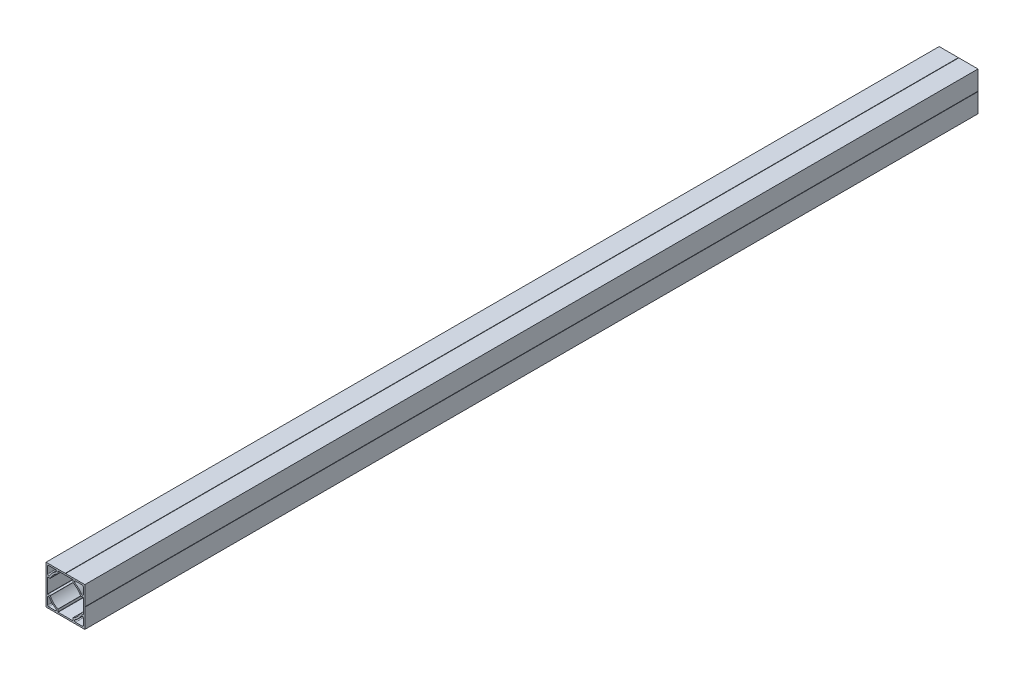
SolidWorks part; units mm, degrees
material "6061 Alloy"
ref_plane "Front Plane" through (0, 0, 0) normal (0, 0, 1) x (1, 0, 0)
ref_plane "Top Plane" through (0, 0, 0) normal (0, 1, 0) x (1, 0, 0)
ref_plane "Right Plane" through (0, 0, 0) normal (1, 0, 0) x (0, 0, -1)
other "Configuration Table"
sketch "Sketch1" plane through (0, 0, 0) normal (0, 0, 1) x (1, 0, 0)
  line L6 (1.7076, 1.016) -> (6.1029, 1.016)
  line L7 (1.016, 6.1029) -> (1.016, 1.7076)
  line L10 (25.4, 12.827) -> (25.4, 25.4)
  line L11 (25.4, 25.4) -> (12.827, 25.4)
  line L14 (12.573, 25.4) -> (0, 25.4)
  line L15 (0, 25.4) -> (0, 12.827)
  line L16 (0, 12.827) -> (0.127, 12.7)
  line L17 (0.127, 12.7) -> (0, 12.573)
  line L18 (0, 12.573) -> (0, 0)
  line L22 (12.827, 0) -> (25.4, 0)
  line L23 (25.4, 0) -> (25.4, 12.573)
  line L24 (1.143, 7.8105) -> (2.6421, 7.8105)
  line L25 (1.016, 17.4625) -> (1.016, 7.9375)
  line L26 (2.6421, 17.5895) -> (1.143, 17.5895)
  line L27 (1.016, 23.6924) -> (1.016, 19.2971)
  line L28 (6.1029, 24.384) -> (1.7076, 24.384)
  line L29 (17.5895, 22.7579) -> (17.5895, 24.257)
  line L30 (17.4625, 24.384) -> (7.9375, 24.384)
  line L31 (7.8105, 24.257) -> (7.8105, 22.7579)
  line L32 (23.6924, 24.384) -> (19.2971, 24.384)
  line L33 (24.384, 19.2971) -> (24.384, 23.6924)
  line L34 (22.7579, 7.8105) -> (24.257, 7.8105)
  line L35 (24.384, 7.9375) -> (24.384, 17.4625)
  line L36 (24.257, 17.5895) -> (22.7579, 17.5895)
  line L37 (24.384, 1.7076) -> (24.384, 6.1029)
  line L38 (19.2971, 1.016) -> (23.6924, 1.016)
  line L39 (7.8105, 2.6421) -> (7.8105, 1.143)
  line L40 (7.9375, 1.016) -> (17.4625, 1.016)
  line L41 (17.5895, 1.143) -> (17.5895, 2.6421)
  line L44 (12.827, 25.4) -> (12.7, 25.273)
  line L45 (12.7, 25.273) -> (12.573, 25.4)
  line L46 (25.4, 12.573) -> (25.273, 12.7)
  line L47 (25.273, 12.7) -> (25.4, 12.827)
  line L48 (12.573, 0) -> (12.7, 0.127)
  line L49 (12.7, 0.127) -> (12.827, 0)
  line L50 (12.573, 0) -> (0, 0)
  arc A14 (1.016, 1.7076) -> (1.7076, 1.016) centre (1.7076, 1.7076) ccw
  arc A15 (2.3006, 6.4588) -> (1.016, 6.1029) centre (1.7076, 6.1029) ccw
  arc A16 (2.3006, 6.4588) -> (6.4588, 2.3006) centre (12.7, 12.7) ccw
  arc A17 (6.1029, 1.016) -> (6.4588, 2.3006) centre (6.1029, 1.7076) ccw
  arc A18 (2.7558, 7.7402) -> (7.7402, 2.7558) centre (12.7, 12.7) ccw
  arc A19 (2.7558, 7.7402) -> (2.6421, 7.8105) centre (2.6421, 7.6835) ccw
  arc A20 (1.016, 7.9375) -> (1.143, 7.8105) centre (1.143, 7.9375) ccw
  arc A21 (1.143, 17.5895) -> (1.016, 17.4625) centre (1.143, 17.4625) ccw
  arc A22 (2.6421, 17.5895) -> (2.7558, 17.6598) centre (2.6421, 17.7165) ccw
  arc A23 (1.016, 19.2971) -> (2.3006, 18.9412) centre (1.7076, 19.2971) ccw
  arc A24 (6.4588, 23.0994) -> (2.3006, 18.9412) centre (12.7, 12.7) ccw
  arc A25 (6.4588, 23.0994) -> (6.1029, 24.384) centre (6.1029, 23.6924) ccw
  arc A26 (1.7076, 24.384) -> (1.016, 23.6924) centre (1.7076, 23.6924) ccw
  arc A27 (17.5895, 24.257) -> (17.4625, 24.384) centre (17.4625, 24.257) ccw
  arc A28 (17.5895, 22.7579) -> (17.6598, 22.6442) centre (17.7165, 22.7579) ccw
  arc A29 (7.9375, 24.384) -> (7.8105, 24.257) centre (7.9375, 24.257) ccw
  arc A30 (7.7402, 22.6442) -> (7.8105, 22.7579) centre (7.6835, 22.7579) ccw
  arc A31 (7.7402, 22.6442) -> (2.7558, 17.6598) centre (12.7, 12.7) ccw
  arc A32 (19.2971, 24.384) -> (18.9412, 23.0994) centre (19.2971, 23.6924) ccw
  arc A33 (23.0994, 18.9412) -> (18.9412, 23.0994) centre (12.7, 12.7) ccw
  arc A34 (23.0994, 18.9412) -> (24.384, 19.2971) centre (23.6924, 19.2971) ccw
  arc A35 (24.384, 23.6924) -> (23.6924, 24.384) centre (23.6924, 23.6924) ccw
  arc A36 (24.257, 7.8105) -> (24.384, 7.9375) centre (24.257, 7.9375) ccw
  arc A37 (22.7579, 7.8105) -> (22.6442, 7.7402) centre (22.7579, 7.6835) ccw
  arc A38 (24.384, 17.4625) -> (24.257, 17.5895) centre (24.257, 17.4625) ccw
  arc A39 (22.6442, 17.6598) -> (22.7579, 17.5895) centre (22.7579, 17.7165) ccw
  arc A40 (22.6442, 17.6598) -> (17.6598, 22.6442) centre (12.7, 12.7) ccw
  arc A41 (24.384, 6.1029) -> (23.0994, 6.4588) centre (23.6924, 6.1029) ccw
  arc A42 (18.9412, 2.3006) -> (23.0994, 6.4588) centre (12.7, 12.7) ccw
  arc A43 (18.9412, 2.3006) -> (19.2971, 1.016) centre (19.2971, 1.7076) ccw
  arc A44 (23.6924, 1.016) -> (24.384, 1.7076) centre (23.6924, 1.7076) ccw
  arc A45 (7.8105, 1.143) -> (7.9375, 1.016) centre (7.9375, 1.143) ccw
  arc A46 (7.8105, 2.6421) -> (7.7402, 2.7558) centre (7.6835, 2.6421) ccw
  arc A47 (17.4625, 1.016) -> (17.5895, 1.143) centre (17.4625, 1.143) ccw
  arc A48 (17.6598, 2.7558) -> (17.5895, 2.6421) centre (17.7165, 2.6421) ccw
  arc A49 (17.6598, 2.7558) -> (22.6442, 7.7402) centre (12.7, 12.7) ccw
  point P41 (12.7, 24.384)
  point P109 (12.7, 12.7)
  point P116 (12.7, 12.7)
  dimension "D1" = 25.4
  dimension "D2" = 1.016
  dimension "D3" = 4
  dimension "D4" = 1.016
  dimension "D7" = 0.127
  dimension "D12" = 11.1125
  dimension "D5" = 0.127
  dimension "D13" = 12.1285
  dimension "D6" = 9.525
  dimension "D8" = 135
  dimension "D9" = 5.7785
  dimension "D10" = 0.127
  dimension "D11" = 4
extrude "Boss-Extrude1" add sketch "Sketch1" along normal blind 584.2
sketch "Sketch2" [suppressed] plane through (0, 0, 0) normal (-1, 0, 0) x (0, 0, 1)
  line L0 (1193.8, 12.7) -> (0, 12.7) construction
  line L1 (0, 12.573) -> (0, 0) construction
  circle A0 centre (12.7, 12.7) radius 2.54
  dimension "D1" = 5.08
  dimension "D2" = 12.7
extrude "Cut-Extrude1" [suppressed] cut sketch "Sketch2" against normal through all
pattern_circular "CirPattern1" [suppressed] count 4 over 360
pattern_linear "LPattern1" [suppressed] count 95 spacing 12.7
equation "\"Length\" = 23"
equation "\"D1@Boss-Extrude1\"=\"Length\""
